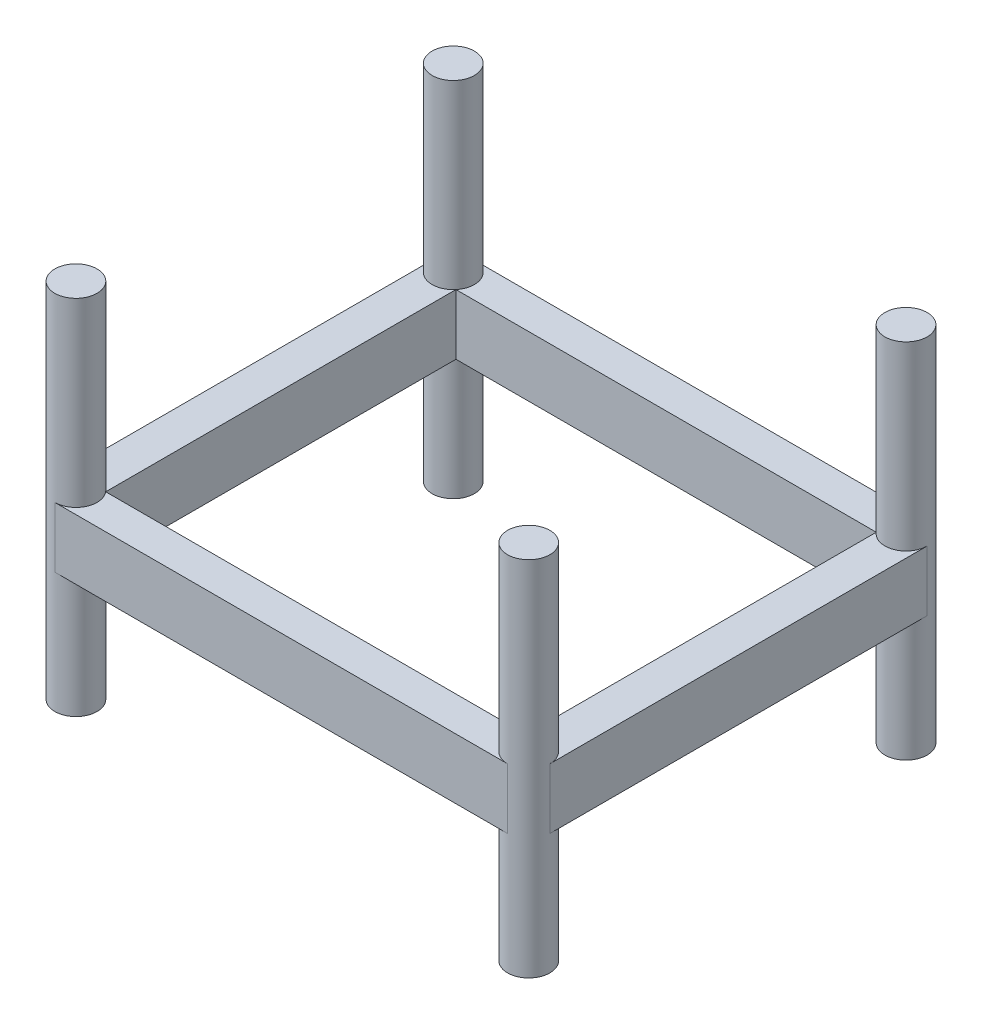
SolidWorks part; units mm, degrees
ref_plane "Front Plane" through (0, 0, 0) normal (0, 0, 1) x (1, 0, 0)
ref_plane "Top Plane" through (0, 0, 0) normal (0, 1, 0) x (1, 0, 0)
ref_plane "Right Plane" through (0, 0, 0) normal (1, 0, 0) x (0, 0, -1)
sketch "Sketch2" plane through (0, 0, 0) normal (0, 1, 0) x (1, 0, 0)
  line L1 (-19.05, -15.875) -> (19.05, -15.875) construction
  line L2 (-19.05, -15.875) -> (-19.05, 15.875) construction
  line L3 (-19.05, 15.875) -> (19.05, 15.875) construction
  line L4 (19.05, -15.875) -> (19.05, 15.875) construction
  line L5 (-19.05, -15.875) -> (19.05, 15.875) construction
  line L6 (-19.05, 15.875) -> (19.05, -15.875) construction
  line L8 (-20.828, -15.875) -> (-20.828, 15.875)
  line L10 (-17.6841, -14.7368) -> (-17.6841, 14.7368)
  line L11 (-17.6841, -14.7368) -> (17.6841, -14.7368)
  line L13 (-19.05, -17.653) -> (19.05, -17.653)
  line L15 (-19.05, 17.653) -> (19.05, 17.653)
  line L17 (-17.6841, 14.7368) -> (17.6841, 14.7368)
  line L20 (20.828, 15.875) -> (20.828, -15.875)
  line L22 (17.6841, 14.7368) -> (17.6841, -14.7368)
  arc A0 (-20.828, -15.875) -> (-19.05, -17.653) centre (-19.05, -15.875) ccw
  arc A2 (20.828, 15.875) -> (19.05, 17.653) centre (19.05, 15.875) ccw
  arc A3 (-19.05, 17.653) -> (-20.828, 15.875) centre (-19.05, 15.875) ccw
  arc A4 (19.05, -17.653) -> (20.828, -15.875) centre (19.05, -15.875) ccw
  point P0 (0, 0)
  point P6 (0, 0)
  dimension "D3" = 3.556
  dimension "D4" = 3.556
  dimension "D5" = 1.778
  dimension "D6" = 3.556
  dimension "D1" = 31.75
  dimension "D2" = 38.1
extrude "Boss-Extrude1" add sketch "Sketch2" along normal blind 5.08
sketch "Sketch3" plane through (0, 5.08, 0) normal (0, 1, 0) x (1, 0, 0)
  circle A0 centre (-19.05, -15.875) radius 1.778
  circle A1 centre (19.05, -15.875) radius 1.778
  circle A2 centre (19.05, 15.875) radius 1.778
  circle A3 centre (-19.05, 15.875) radius 1.778
  arc A6 (-20.828, -15.875) -> (-19.05, -17.653) centre (-19.05, -15.875) ccw construction
  arc A7 (-19.05, 17.653) -> (-20.828, 15.875) centre (-19.05, 15.875) ccw construction
  arc A8 (20.828, 15.875) -> (19.05, 17.653) centre (19.05, 15.875) ccw construction
  arc A9 (19.05, -17.653) -> (20.828, -15.875) centre (19.05, -15.875) ccw construction
  point P0 (0, 0)
  dimension "D1" = 3.556
  dimension "D2" = 3.556
  dimension "D3" = 3.556
  dimension "D4" = 3.556
  dimension "D5" = 31.75
  dimension "D6" = 38.1
extrude "Boss-Extrude2" add sketch "Sketch3" along normal blind 15.24 and the other way blind 15.24
